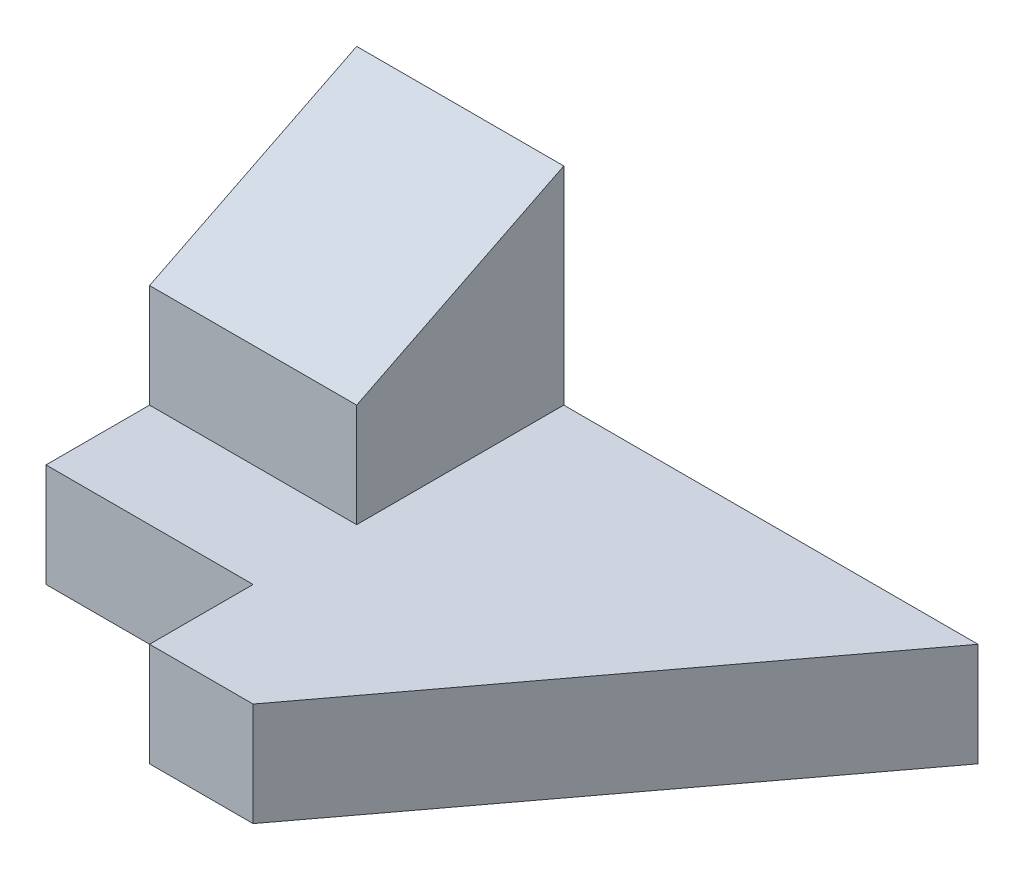
SolidWorks part; units mm, degrees
ref_plane "前基準面" through (0, 0, 0) normal (0, 0, 1) x (1, 0, 0)
ref_plane "上基準面" through (0, 0, 0) normal (0, 1, 0) x (1, 0, 0)
ref_plane "右基準面" through (0, 0, 0) normal (1, 0, 0) x (0, 0, -1)
sketch "草圖1" plane through (0, 0, 0) normal (0, 1, 0) x (1, 0, 0)
  line L0 (0, 0) -> (30, 0)
  line L1 (30, 0) -> (15, -20)
  line L2 (15, -20) -> (10, -20)
  line L3 (10, -20) -> (10, -15)
  line L4 (10, -15) -> (0, -15)
  line L5 (0, -15) -> (0, 0)
  dimension "D1" = 30
  dimension "D2" = 15
  dimension "D3" = 10
  dimension "D4" = 5
  dimension "D5" = 20
  dimension "D6" = 15
extrude "填料-伸長1" add sketch "草圖1" along normal blind 5
sketch "草圖2" plane through (0, 0, 0) normal (-1, 0, 0) x (0, 0, 1)
  line L0 (0, 5) -> (0, 15)
  line L1 (0, 15) -> (10, 10)
  line L2 (10, 10) -> (10, 5)
  line L3 (0, 5) -> (15, 5) construction
  line L4 (10, 5) -> (0, 5)
  dimension "D1" = 5
  dimension "D2" = 10
  dimension "D3" = 10
extrude "填料-伸長2" add sketch "草圖2" against normal blind 10
